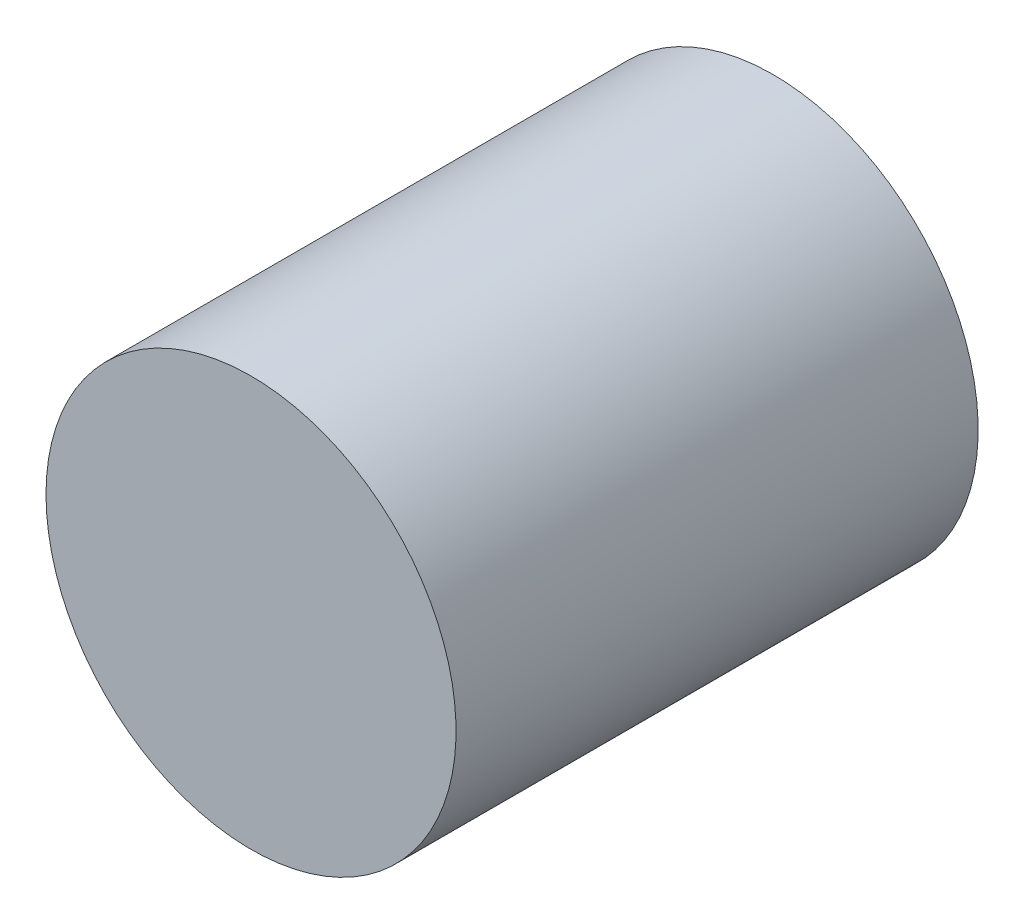
SolidWorks part; units mm, degrees
ref_plane "前视基准面" through (0, 0, 0) normal (0, 0, 1) x (1, 0, 0)
ref_plane "上视基准面" through (0, 0, 0) normal (0, 1, 0) x (1, 0, 0)
ref_plane "右视基准面" through (0, 0, 0) normal (1, 0, 0) x (0, 0, -1)
other "Configuration Table"
sketch "草图1" plane through (0, 0, 0) normal (0, 0, 1) x (1, 0, 0)
  circle A0 centre (0, 0) radius 47.1207
extrude "凸台-拉伸1" add sketch "草图1" along normal blind 120
